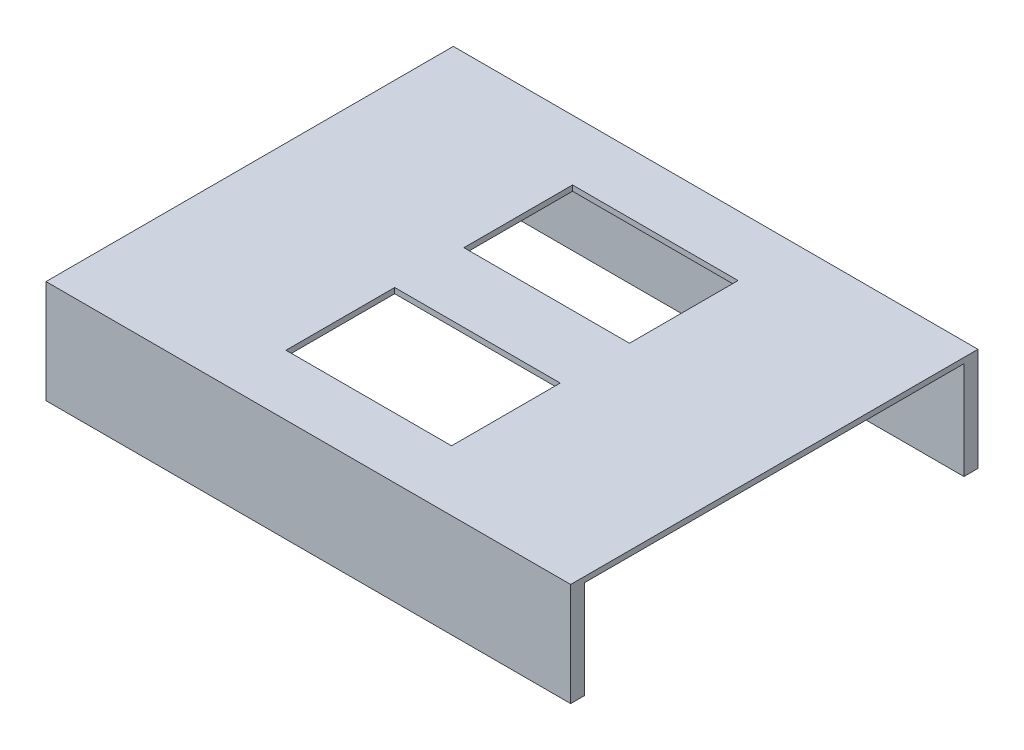
SolidWorks part; units mm, degrees
ref_plane "Front Plane" through (0, 0, 0) normal (0, 0, 1) x (1, 0, 0)
ref_plane "Top Plane" through (0, 0, 0) normal (0, 1, 0) x (1, 0, 0)
ref_plane "Right Plane" through (0, 0, 0) normal (1, 0, 0) x (0, 0, -1)
sketch "Sketch1" plane through (0, 0, 0) normal (0, 1, 0) x (1, 0, 0)
  line L1 (-216.4826, 101.735) -> (266.5174, 101.735)
  line L2 (-216.4826, 101.735) -> (-216.4826, -273.265)
  line L3 (-216.4826, -273.265) -> (266.5174, -273.265)
  line L4 (266.5174, 101.735) -> (266.5174, -273.265)
  dimension "D1" = 375
  dimension "D2" = 483
extrude "Boss-Extrude1" add sketch "Sketch1" along normal blind 95 contours L2 L1 L4 L3
sketch "Sketch2" plane through (-216.4826, 0, 0) normal (-1, 0, 0) x (0, 0, 1)
  line L0 (-101.735, 0) -> (273.265, 0) construction
  line L1 (-88.7696, 90) -> (260.311, 90)
  line L2 (-88.7696, 90) -> (-88.7696, 0)
  line L3 (-88.7696, 0) -> (260.311, 0)
  line L4 (260.311, 90) -> (260.311, 0)
  line L5 (-101.735, 95) -> (-101.735, 0) construction
  line L6 (273.265, 95) -> (273.265, 0) construction
  line L7 (-101.735, 95) -> (273.265, 95) construction
  dimension "D1" = 12.9654
  dimension "D2" = 12.954
  dimension "D3" = 5
extrude "Cut-Extrude1" cut sketch "Sketch2" against normal blind 531.118
sketch "Sketch3" plane through (0, 95, 0) normal (0, 1, 0) x (1, 0, 0)
  line L0 (-216.4826, -273.265) -> (266.5174, -273.265) construction
  line L1 (-51.1286, 46.109) -> (101.2714, 46.109)
  line L2 (-51.1286, 46.109) -> (-51.1286, -53.891)
  line L3 (-51.1286, -53.891) -> (101.2714, -53.891)
  line L4 (101.2714, 46.109) -> (101.2714, -53.891)
  line L5 (-51.2556, -117.4784) -> (101.1444, -117.4784)
  line L6 (-51.2556, -117.4784) -> (-51.2556, -217.5544)
  line L7 (-51.2556, -217.5544) -> (101.1444, -217.5544)
  line L8 (101.1444, -117.4784) -> (101.1444, -217.5544)
  line L9 (-216.4826, 101.735) -> (266.5174, 101.735) construction
  line L10 (-216.4826, 101.735) -> (-216.4826, -273.265) construction
  dimension "D1" = 100
  dimension "D2" = 152.4
  dimension "D3" = 152.4
  dimension "D4" = 100.076
  dimension "D5" = 55.7106
  dimension "D6" = 55.626
  dimension "D7" = 165.227
  dimension "D8" = 165.354
extrude "Cut-Extrude2" cut sketch "Sketch3" against normal blind 531.118 contours L2 L1 L4 L3 | L6 L5 L8 L7
